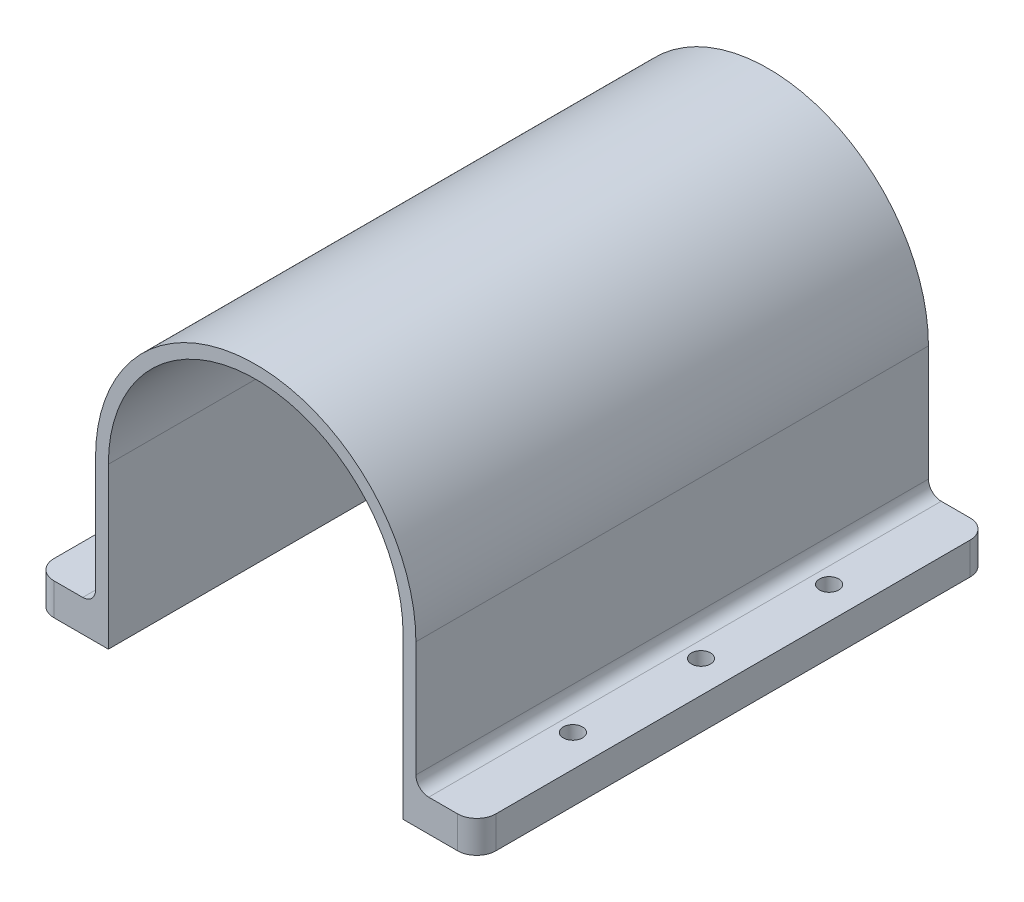
SolidWorks part; units mm, degrees
ref_plane "Front Plane" through (0, 0, 0) normal (0, 0, 1) x (1, 0, 0)
ref_plane "Top Plane" through (0, 0, 0) normal (0, 1, 0) x (1, 0, 0)
ref_plane "Right Plane" through (0, 0, 0) normal (1, 0, 0) x (0, 0, -1)
sketch "Sketch1" plane through (0, 0, 0) normal (0, 0, 1) x (1, 0, 0)
  line L0 (-25, 0) -> (-25, -20)
  line L1 (-25, -20) -> (-34.5, -20)
  line L2 (-34.5, -20) -> (-34.5, -25)
  line L3 (-34.5, -25) -> (34.5, -25)
  line L4 (25, 0) -> (25, -20)
  line L5 (25, -20) -> (34.5, -20)
  line L6 (34.5, -20) -> (34.5, -25)
  line L7 (0, 29.2864) -> (0, -39.5899) construction
  line L8 (-26.278, 26.278) -> (26.278, -26.278) construction
  circle A0 centre (0, 0) radius 22.5 construction
  arc A1 (25, 0) -> (-25, 0) centre (0, 0) ccw
  circle A2 centre (-12.4097, 12.4097) radius 2
  circle A3 centre (12.4097, 12.4097) radius 2
  circle A4 centre (12.4097, -12.4097) radius 2
  circle A5 centre (-12.4097, -12.4097) radius 2
  circle A6 centre (0, 0) radius 13
  point P9 (0, -25)
  point P16 (0, 0)
  point P28 (0, 0)
  dimension "D1" = 45
  dimension "D2" = 50
  dimension "D6" = 4
  dimension "D9" = 26
  dimension "D3" = 5
  dimension "D4" = 69
  dimension "D5" = 45
  dimension "D7" = 17.55
  dimension "D8" = 4
extrude "Boss-Extrude1" add sketch "Sketch1" along normal blind 80
sketch "Sketch2" plane through (0, 0, 80) normal (0, 0, 1) x (1, 0, 0)
  line L0 (-23, 0) -> (-23, -25)
  line L1 (-34.5, -25) -> (34.5, -25) construction
  line L2 (23, 0) -> (23, -25)
  line L3 (23, -25) -> (-23, -25)
  arc A0 (23, 0) -> (-23, 0) centre (0, 0) ccw
  dimension "D1" = 46
extrude "Cut-Extrude1" cut sketch "Sketch2" against normal blind 75
sketch "Sketch3" plane through (0, -20, 0) normal (0, 1, 0) x (1, 0, 0)
  line L0 (0, 0) -> (0, -80) construction
  line L1 (-25, -80) -> (25, -80) construction
  line L2 (29.5, 0) -> (29.5, -80) construction
  line L3 (34.5, 0) -> (25, 0) construction
  line L4 (34.5, -80) -> (25, -80) construction
  line L5 (34.5, -80) -> (34.5, 0) construction
  circle A0 centre (29.5, -40) radius 1.5
  circle A1 centre (29.5, -60) radius 1.5
  circle A2 centre (29.5, -20) radius 1.5
  circle A3 centre (-29.5, -60) radius 1.5
  circle A4 centre (-29.5, -40) radius 1.5
  circle A5 centre (-29.5, -20) radius 1.5
  dimension "D2" = 3
  dimension "D1" = 5
  dimension "D3" = 20
  dimension "D4" = 20
extrude "Cut-Extrude2" cut sketch "Sketch3" against normal through all both and the other way through all
fillet "Fillet3" radius 2 2 edges at (25, -20, 40) (-25, -20, 40)
fillet "Fillet2" radius 3 4 edges at (34.5, -22.5, 80) (34.5, -22.5, 0) (-34.5, -22.5, 0) (-34.5, -22.5, 80)
